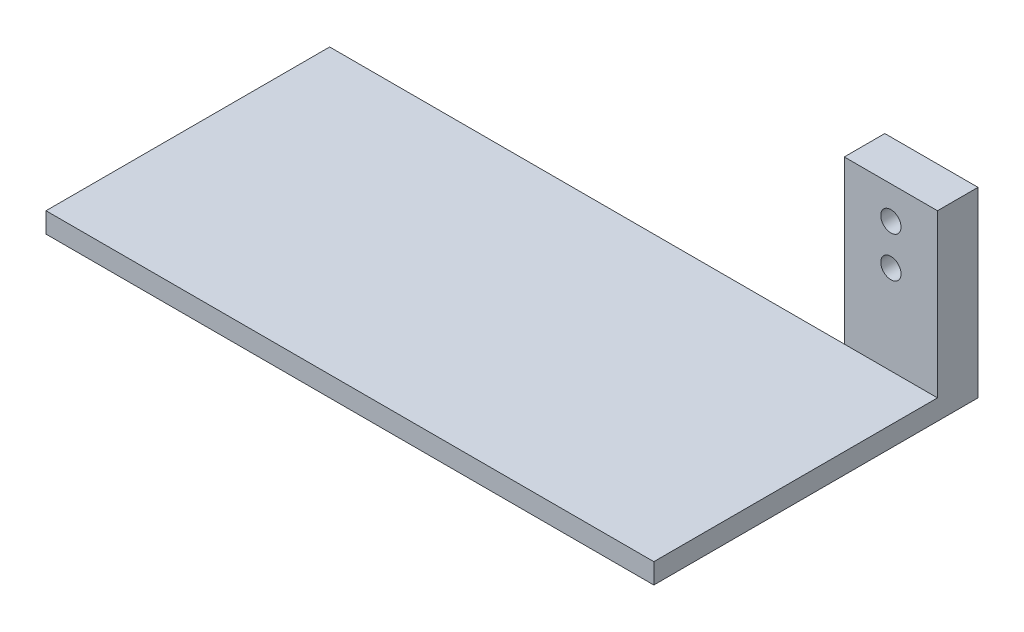
SolidWorks part; units mm, degrees
material "1060 Alloy"
ref_plane "Front Plane" through (0, 0, 0) normal (0, 0, 1) x (1, 0, 0)
ref_plane "Top Plane" through (0, 0, 0) normal (0, 1, 0) x (1, 0, 0)
ref_plane "Right Plane" through (0, 0, 0) normal (1, 0, 0) x (0, 0, -1)
sketch "Sketch2" plane through (0, 0, 0) normal (0, 1, 0) x (1, 0, 0)
  line L5 (-11.5, 5) -> (11.5, 5)
  line L6 (-11.5, 5) -> (-11.5, -5)
  line L7 (-11.5, -5) -> (11.5, -5)
  line L8 (11.5, 5) -> (11.5, -5)
  line L9 (-11.5, 5) -> (11.5, -5) construction
  line L10 (-11.5, -5) -> (11.5, 5) construction
  point P0 (0, 0)
  dimension "D1" = 23
  dimension "D2" = 10
extrude "Boss-Extrude1" add sketch "Sketch2" along normal blind 40
sketch "Sketch3" plane through (0, 0, 5) normal (0, 0, 1) x (1, 0, 0)
  line L0 (-11.5, 40) -> (11.5, 40) construction
  line L1 (-11.5, 40) -> (-11.5, 0) construction
  circle A0 centre (0, 32) radius 2.5
  circle A1 centre (0, 22) radius 2.5
  dimension "D1" = 5
  dimension "D2" = 5
  dimension "D3" = 8
  dimension "D4" = 10
  dimension "D5" = 11.5
extrude "Cut-Extrude1" cut sketch "Sketch3" against normal through all
sketch "Sketch4" plane through (0, 0, 5) normal (0, 0, 1) x (1, 0, 0)
  line L0 (11.5, 40) -> (11.5, 0) construction
  line L1 (-138.5, 0) -> (11.5, 0)
  line L2 (-138.5, 0) -> (-138.5, -5)
  line L3 (-138.5, -5) -> (11.5, -5)
  line L4 (11.5, 0) -> (11.5, -5)
  line L5 (-138.5, 0) -> (11.5, -5) construction
  line L6 (-138.5, -5) -> (11.5, 0) construction
  line L7 (-11.5, 0) -> (11.5, 0) construction
  point P0 (-63.5, -2.5)
  dimension "D1" = 150
  dimension "D2" = 5
extrude "Boss-Extrude2" add sketch "Sketch4" along normal blind 70
sketch "Sketch5" plane through (0, 0, 0) normal (0, -1, 0) x (1, 0, 0)
  line L4 (11.5, -5) -> (11.5, 5)
  line L5 (11.5, 5) -> (-11.5, 5)
  line L6 (-11.5, 5) -> (-11.5, -5)
  line L7 (-11.5, -5) -> (11.5, -5)
  line L8 (11.5, -5) -> (11.5, 5)
  line L9 (11.5, 5) -> (-11.5, 5)
  line L10 (-11.5, 5) -> (-11.5, -5)
  line L11 (-11.5, -5) -> (11.5, -5)
  dimension "D1" = 0
extrude "Boss-Extrude3" add sketch "Sketch5" along normal blind 5
